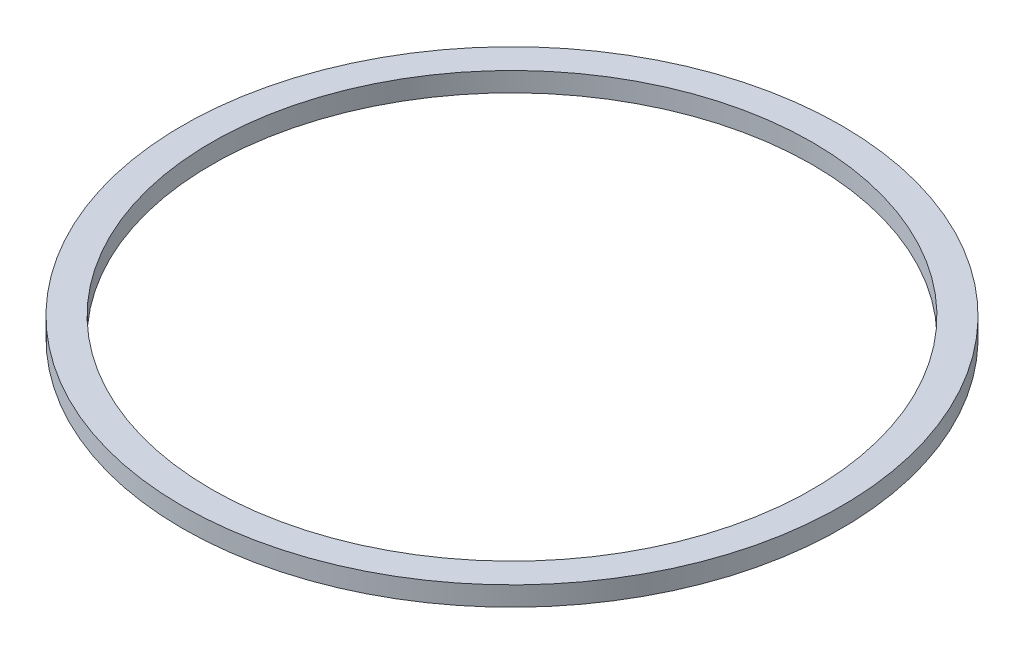
SolidWorks part; units mm, degrees
ref_plane "Plan de face" through (0, 0, 0) normal (0, 0, 1) x (1, 0, 0)
ref_plane "Plan de dessus" through (0, 0, 0) normal (0, 1, 0) x (1, 0, 0)
ref_plane "Plan de droite" through (0, 0, 0) normal (1, 0, 0) x (0, 0, -1)
sketch "Esquisse1" plane through (0, 0, 0) normal (0, 1, 0) x (1, 0, 0)
  circle A0 centre (0, 0) radius 17
  circle A1 centre (0, 0) radius 15.5
  dimension "D1" = 31
  dimension "D2" = 34
extrude "Boss.-Extru.1" add sketch "Esquisse1" along normal blind 1
